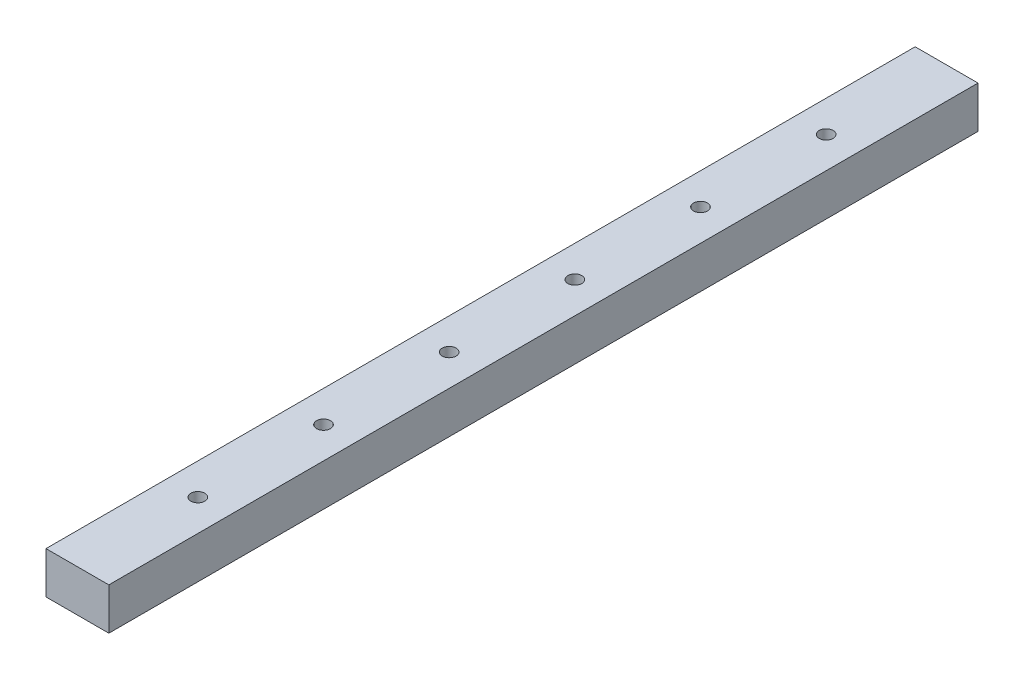
SolidWorks part; units mm, degrees
ref_plane "Front Plane" through (0, 0, 0) normal (0, 0, 1) x (1, 0, 0)
ref_plane "Top Plane" through (0, 0, 0) normal (0, 1, 0) x (1, 0, 0)
ref_plane "Right Plane" through (0, 0, 0) normal (1, 0, 0) x (0, 0, -1)
sketch "Sketch1" plane through (0, 0, 0) normal (0, 0, 1) x (1, 0, 0)
  line L1 (22.225, -12.7) -> (-22.225, -12.7)
  line L2 (22.225, -12.7) -> (22.225, 12.7)
  line L3 (22.225, 12.7) -> (-22.225, 12.7)
  line L4 (-22.225, -12.7) -> (-22.225, 12.7)
  line L5 (22.225, -12.7) -> (-22.225, 12.7) construction
  line L6 (22.225, 12.7) -> (-22.225, -12.7) construction
  line L7 (22.225, 12.7) -> (15.875, 12.7)
  line L8 (22.225, 12.7) -> (22.225, -12.7)
  line L9 (22.225, -12.7) -> (15.875, -12.7)
  line L10 (15.875, 12.7) -> (15.875, -12.7)
  point P0 (0, 0)
  dimension "D1" = 25.4
  dimension "D2" = 44.45
  dimension "D3" = 6.35
  dimension "D4" = 25.4
extrude "Boss-Extrude1" add sketch "Sketch1" along normal blind 527.05 contours L10 L3 L4 L1 L2 L9
hole_wizard "CSK for 5/16 Flat Head Machine Screw1" positions "Sketch2" profile "Sketch3" countersink size "5/16" standard "ANSI Inch" end condition through all
sketch "Sketch2" plane through (0, -12.7, 0) normal (0, -1, 0) x (-1, 0, 0)
  line L0 (-15.875, -527.05) -> (22.225, -527.05) construction
  line L1 (22.225, -527.05) -> (22.225, 0) construction
  line L2 (-15.875, 0) -> (22.225, 0) construction
  point P0 (3.175, -454.025)
  point P15 (3.175, -377.825)
  point P16 (3.175, -301.625)
  point P17 (3.175, -225.425)
  point P18 (3.175, -149.225)
  point P19 (3.175, -73.025)
  dimension "D1" = 73.025
  dimension "D2" = 19.05
  dimension "D4" = 73.025
  dimension "D3" = 6
sketch "Sketch3" plane through (-3.175, -12.7, 454.025) normal (1, 0, 0) x (0, 0, -1)
  line L0 (0, 0) -> (0, 25.4)
  line L1 (0, 25.4) -> (4.2164, 25.4)
  line L2 (4.2164, 25.4) -> (4.2164, 4.4267)
  line L3 (4.2164, 4.4267) -> (8.0645, 0)
  line L5 (8.0645, 0) -> (0, 0)
  line L6 (-4.2164, 4.4267) -> (-8.0645, 0) construction
  line L11 (0, -6.35) -> (0, 107.95) construction
  dimension "Thru Hole Dia." = 8.4328
  dimension "Thru Hole Depth" = 25.4
  dimension "Near C'Sink Dia." = 16.129
  dimension "Near C'Sink Angle" = 82
